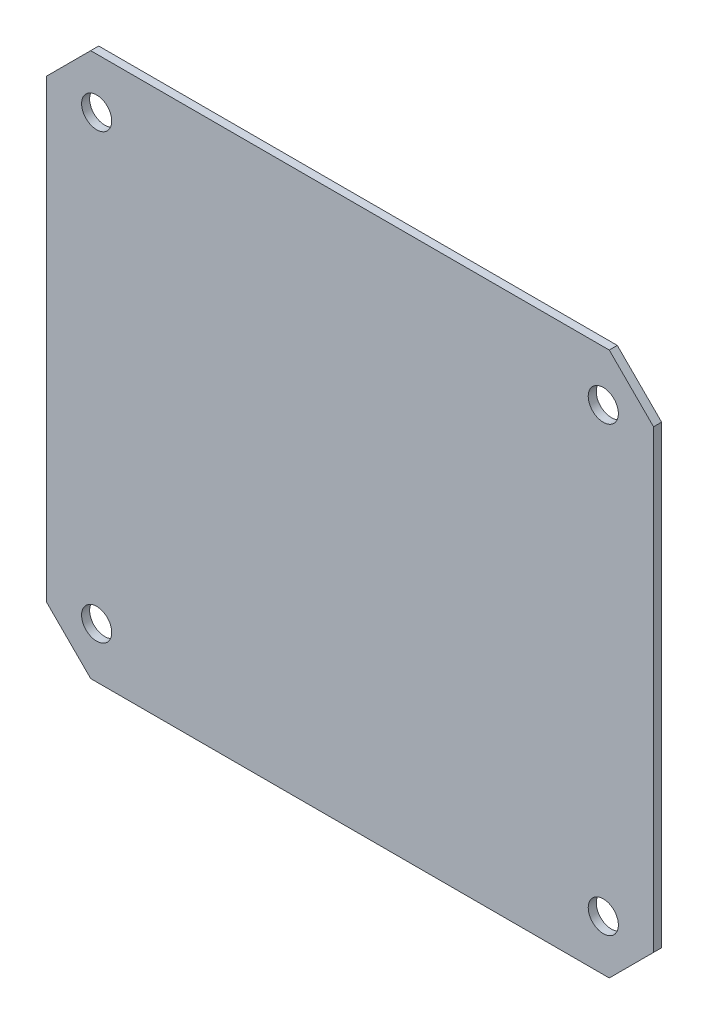
SolidWorks part; units mm, degrees
ref_plane "前基準面" through (0, 0, 0) normal (0, 0, 1) x (1, 0, 0)
ref_plane "上基準面" through (0, 0, 0) normal (0, 1, 0) x (1, 0, 0)
ref_plane "右基準面" through (0, 0, 0) normal (1, 0, 0) x (0, 0, -1)
sketch "草圖1" plane through (0, 0, 0) normal (0, 0, 1) x (1, 0, 0)
  line L0 (-29.2, 22.23) -> (-25.38, 26.05) construction
  line L1 (-29.2, 26.05) -> (29.2, 26.05) construction
  line L2 (-29.2, 26.05) -> (-29.2, -26.05) construction
  line L3 (-29.2, -26.05) -> (29.2, -26.05) construction
  line L4 (29.2, 26.05) -> (29.2, -26.05) construction
  line L5 (0, 26.05) -> (0, -26.05) construction
  line L6 (-29.2, 0) -> (29.2, 0) construction
  line L7 (-29.4, 22.3128) -> (-25.4628, 26.25)
  line L8 (-29.3414, 22.3714) -> (-25.5214, 26.1914) construction
  line L9 (29.4, 22.3128) -> (25.4628, 26.25)
  line L10 (-29.4, 22.3128) -> (-29.4, -22.3128)
  line L11 (-25.4628, -26.25) -> (25.4628, -26.25)
  line L12 (29.4, 22.3128) -> (29.4, -22.3128)
  line L13 (-25.4628, 26.25) -> (25.4628, 26.25)
  line L14 (29.4, -22.3128) -> (25.4628, -26.25)
  line L15 (-29.4, -22.3128) -> (-25.4628, -26.25)
  line L16 (-25.7942, 27.05) -> (25.7942, 27.05)
  line L17 (-29.4, 26.25) -> (29.4, 26.25) construction
  line L18 (-29.4, 26.25) -> (-29.4, -26.25) construction
  line L19 (-29.4, -26.25) -> (29.4, -26.25) construction
  line L20 (29.4, 26.25) -> (29.4, -26.25) construction
  line L21 (30.2, 22.6442) -> (25.7942, 27.05)
  line L22 (30.2, 22.6442) -> (30.2, -22.6442)
  line L23 (30.2, -22.6442) -> (25.7942, -27.05)
  line L24 (-25.7942, -27.05) -> (25.7942, -27.05)
  line L25 (-30.2, -22.6442) -> (-25.7942, -27.05)
  line L26 (-30.2, 22.6442) -> (-30.2, -22.6442)
  line L27 (-30.2, 22.6442) -> (-25.7942, 27.05)
  point P4 (0, 26.05)
  point P6 (-29.2, 0)
  dimension "D1" = 58.4
  dimension "D2" = 52.1
  dimension "D5" = 5.4023
  dimension "D6" = 0.2
  dimension "D7" = 0.2
  dimension "D8" = 0.8
  dimension "D3" = 3.82
  dimension "D4" = 3.82
extrude "填料-伸長1" add sketch "草圖1" along normal blind 22.2
sketch "草圖2" plane through (0, 0, 0) normal (0, 0, -1) x (-1, 0, 0)
  line L0 (-30.2, 22.6442) -> (-25.7942, 27.05)
  line L1 (-25.7942, 27.05) -> (25.7942, 27.05)
  line L2 (25.7942, 27.05) -> (30.2, 22.6442)
  line L3 (30.2, 22.6442) -> (30.2, -22.6442)
  line L4 (30.2, -22.6442) -> (25.7942, -27.05)
  line L5 (25.7942, -27.05) -> (-25.7942, -27.05)
  line L6 (-25.7942, -27.05) -> (-30.2, -22.6442)
  line L7 (-30.2, -22.6442) -> (-30.2, 22.6442)
extrude "填料-伸長2" add sketch "草圖2" along normal blind 4.5
sketch "草圖3" plane through (0, 0, 0) normal (0, 0, 1) x (1, 0, 0)
  line L2 (-30.2, 0) -> (30.2, 0) construction
  line L5 (0, 27.05) -> (0, -27.05) construction
  line L8 (25.7942, 27.05) -> (-25.7942, 27.05) construction
  line L9 (-25.7942, -27.05) -> (25.7942, -27.05) construction
  line L10 (30.2, -22.6442) -> (30.2, 22.6442) construction
  line L11 (-30.2, 22.6442) -> (-30.2, -22.6442) construction
  circle A0 centre (25.2, 22.03) radius 1.5
  circle A1 centre (25.2, -22.03) radius 1.5
  circle A2 centre (-25.2, -22.03) radius 1.5
  circle A3 centre (-25.2, 22.03) radius 1.5
  dimension "D1" = 3
  dimension "D2" = 5.02
  dimension "D3" = 5
extrude "除料-伸長1" cut sketch "草圖3" against normal through all
sketch "草圖5" plane through (0, 0, 0) normal (0, 0, 1) x (1, 0, 0)
  line L0 (-25.2341, 18.5302) -> (-25.2341, -18.5302)
  line L1 (-21.7005, -22.0917) -> (21.7005, -22.0917)
  line L2 (25.2974, -18.5314) -> (25.2974, 18.5314)
  line L3 (21.7461, 22.5961) -> (-21.7461, 22.5961)
  arc A0 (-25.2341, 18.5302) -> (-21.7461, 22.5961) centre (-25.2, 22.03) ccw
  arc A2 (21.7461, 22.5961) -> (25.2974, 18.5314) centre (25.2, 22.03) ccw
  arc A3 (25.2974, -18.5314) -> (21.7005, -22.0917) centre (25.2, -22.03) ccw
  arc A4 (-21.7005, -22.0917) -> (-25.2341, -18.5302) centre (-25.2, -22.03) ccw
  point P9 (22.5643, 19.7272)
  point P30 (22.7378, -19.5426)
  point P31 (-22.5435, 19.7511)
  point P32 (-22.7154, -19.5649)
  dimension "D1" = 7
  dimension "D2" = 3.5
  dimension "D3" = 7
  dimension "D4" = 7
  dimension "D5" = 7
  dimension "D6" = 3.5
  dimension "D7" = 3.5
  dimension "D8" = 3.5
extrude "除料-伸長3" cut sketch "草圖5" against normal blind 3.7
sketch "草圖6" plane through (0, -27.05, 0) normal (0, -1, 0) x (1, 0, 0)
  line L0 (30.2, 22.2) -> (30.2, -4.5) construction
  line L1 (2.2, 8.7) -> (11.2, 8.7)
  line L2 (2.2, 8.7) -> (2.2, 1.1)
  line L3 (2.2, 1.1) -> (11.2, 1.1)
  line L4 (11.2, 8.7) -> (11.2, 1.1)
  line L5 (-17.2, 17.2) -> (-6.2, 17.2)
  line L6 (-17.2, 17.2) -> (-17.2, 11.2)
  line L7 (-17.2, 11.2) -> (-6.2, 11.2)
  line L8 (-6.2, 17.2) -> (-6.2, 11.2)
  line L9 (25.7942, -4.5) -> (-25.7942, -4.5) construction
  line L10 (-25.7942, 22.2) -> (25.7942, 22.2) construction
  line L11 (-30.2, 22.2) -> (-30.2, -4.5) construction
  dimension "D1" = 28
  dimension "D2" = 9
  dimension "D3" = 7.6
  dimension "D4" = 5.6
  dimension "D5" = 5
  dimension "D6" = 6
  dimension "D7" = 13
  dimension "D8" = 11
extrude "除料-伸長4" cut sketch "草圖6" against normal up to next
sketch "草圖7" plane through (0, 27.05, 0) normal (0, 1, 0) x (1, 0, 0)
  line L0 (30.2, -22.2) -> (30.2, 4.5) construction
  line L1 (2.5, -11.35) -> (-2.5, -11.35)
  line L2 (2.5, -11.35) -> (2.5, -6.35)
  line L3 (2.5, -6.35) -> (-2.5, -6.35)
  line L4 (-2.5, -11.35) -> (-2.5, -6.35)
  point P4 (0, -11.35)
  point P8 (30.2, -8.85)
  point P9 (2.5, -8.85)
  dimension "D1" = 5
  dimension "D2" = 5
extrude "除料-伸長5" cut sketch "草圖7" against normal up to next
sketch "草圖8" plane through (0, 0, -4.5) normal (0, 0, -1) x (-1, 0, 0)
  line L0 (30.2, -22.6442) -> (25.7942, -27.05)
  line L1 (25.7942, -27.05) -> (-25.7942, -27.05)
  line L2 (-25.7942, -27.05) -> (-30.2, -22.6442)
  line L3 (-30.2, -22.6442) -> (-30.2, 22.6442)
  line L4 (-30.2, 22.6442) -> (-25.7942, 27.05)
  line L5 (-25.7942, 27.05) -> (25.7942, 27.05)
  line L6 (25.7942, 27.05) -> (30.2, 22.6442)
  line L7 (30.2, 22.6442) -> (30.2, -22.6442)
  circle A0 centre (25.2, -22.03) radius 1.5
  circle A1 centre (-25.2, -22.03) radius 1.5
  circle A2 centre (-25.2, 22.03) radius 1.5
  circle A3 centre (25.2, 22.03) radius 1.5
extrude "填料-伸長3" add sketch "草圖8" along normal blind 0.8
sketch "草圖10" plane through (0, 27.05, 0) normal (0, 1, 0) x (1, 0, 0)
  line L0 (-30.2, -22.2) -> (-30.2, 5.3) construction
  line L1 (-30.2, 4.5) -> (30.2, 4.5)
  line L2 (-30.2, 4.5) -> (-30.2, -22.2)
  line L3 (-30.2, -22.2) -> (30.2, -22.2)
  line L4 (30.2, 4.5) -> (30.2, -22.2)
  line L5 (30.2, -22.2) -> (30.2, 5.3) construction
  line L6 (30.2, -22.2) -> (25.7942, -22.2) construction
  line L7 (-25.7942, 5.3) -> (25.7942, 5.3) construction
  dimension "D1" = 0.8
extrude "除料-伸長7" cut sketch "草圖10" against normal through all
